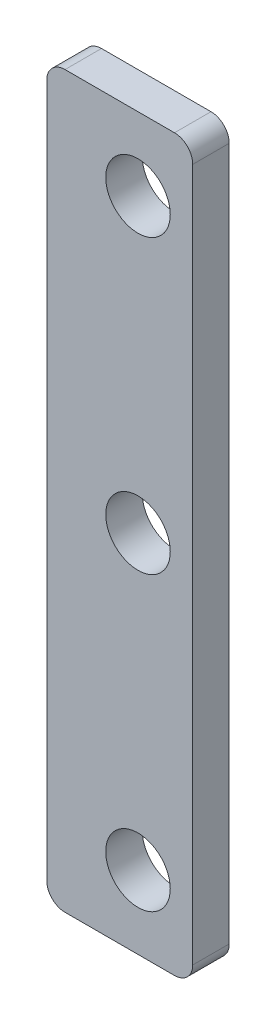
SolidWorks part; units mm, degrees
material "ABS"
ref_plane "Front" through (0, 0, 0) normal (0, 0, 1) x (1, 0, 0)
ref_plane "Top" through (0, 0, 0) normal (0, 1, 0) x (1, 0, 0)
ref_plane "Right" through (0, 0, 0) normal (1, 0, 0) x (0, 0, -1)
sketch "Sketch1" plane through (0, 0, 0) normal (0, 0, 1) x (1, 0, 0)
  line L1 (-6.35, -31.75) -> (6.35, -31.75)
  line L2 (-6.35, -31.75) -> (-6.35, 31.75)
  line L3 (-6.35, 31.75) -> (6.35, 31.75)
  line L4 (6.35, -31.75) -> (6.35, 31.75)
  line L5 (-6.35, -31.75) -> (6.35, 31.75) construction
  line L6 (-6.35, 31.75) -> (6.35, -31.75) construction
  point P0 (0, 0)
  dimension "D1" = 63.5
  dimension "D2" = 12.7
extrude "Boss-Extrude1" add sketch "Sketch1" along normal blind 3.175
hole_wizard "#10 Clearance Hole1" positions "Sketch2" profile "Sketch3" hole size "#10" standard "ANSI Inch"
sketch "Sketch2" plane through (0, 0, 3.175) normal (0, 0, 1) x (1, 0, 0)
  line L0 (1.5875, 31.75) -> (1.5875, -31.75) construction
  line L1 (6.35, 31.75) -> (-6.35, 31.75) construction
  line L2 (-6.35, -31.75) -> (6.35, -31.75) construction
  line L4 (-6.35, 31.75) -> (-6.35, -31.75) construction
  point P11 (1.5875, 0)
  point P13 (1.5875, 25.4)
  point P15 (1.5875, -25.4)
  dimension "D1" = 7.9375
  dimension "D2" = 25.4
  dimension "D3" = 25.4
sketch "Sketch3" plane through (1.5875, -25.4, 3.175) normal (1, 0, 0) x (0, -1, 0)
  line L0 (0, 0) -> (0, 27.0864)
  line L1 (0, 27.0864) -> (2.8067, 25.4)
  line L2 (2.8067, 25.4) -> (2.8067, 0)
  line L5 (2.8067, 0) -> (0, 0)
  line L10 (0, 27.0864) -> (-2.8067, 25.4) construction
  line L11 (0, -6.35) -> (0, 107.95) construction
  dimension "Hole Dia." = 5.6134
  dimension "Hole Depth" = 25.4
  dimension "Drill Angle" = 118
fillet "Fillet1" radius 1.5875 4 edges at (-6.35, -31.75, 1.5875) (6.35, -31.75, 1.5875) (6.35, 31.75, 1.5875) (-6.35, 31.75, 1.5875)
